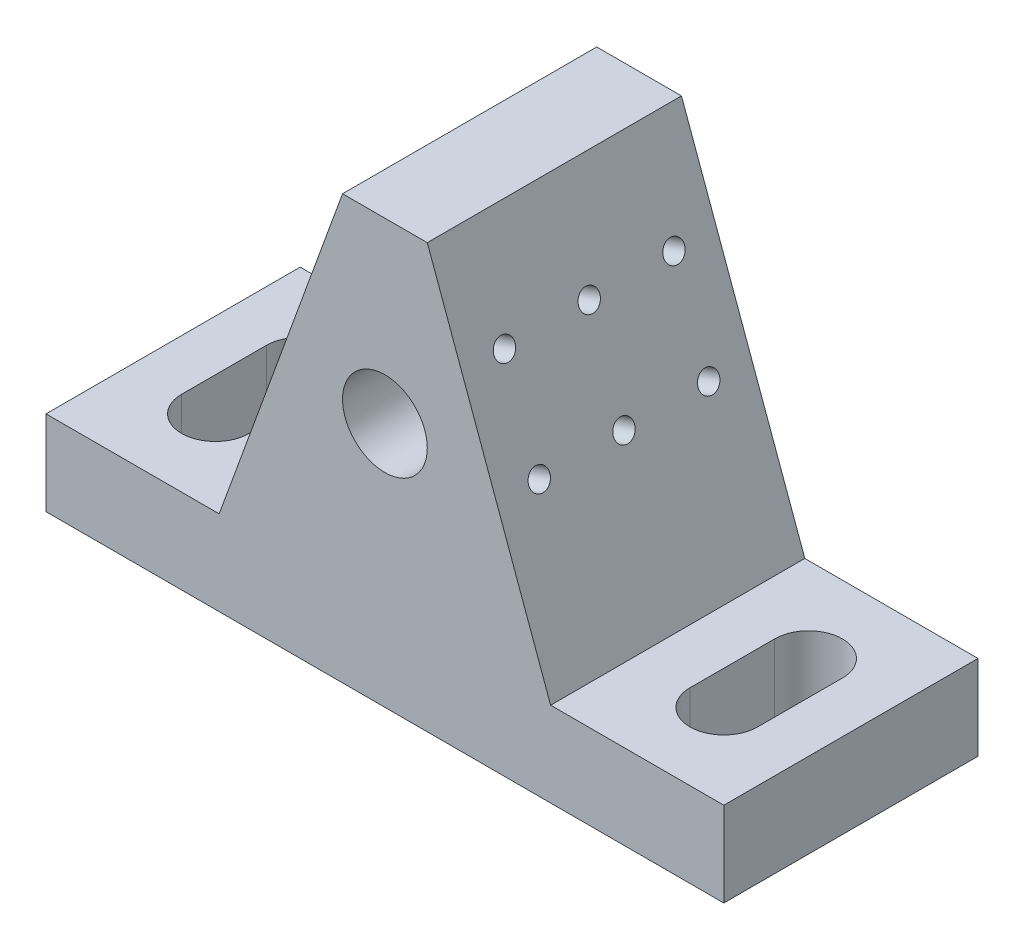
SolidWorks part; units mm, degrees
material "AISI 304"
ref_plane "Front Plane" through (0, 0, 0) normal (0, 0, 1) x (1, 0, 0)
ref_plane "Top Plane" through (0, 0, 0) normal (0, 1, 0) x (1, 0, 0)
ref_plane "Right Plane" through (0, 0, 0) normal (1, 0, 0) x (0, 0, -1)
sketch "Sketch1" plane through (0, 0, 0) normal (0, 0, 1) x (1, 0, 0)
  line L0 (0, 0) -> (0, 44.6241) construction
  line L1 (-40, 0) -> (40, 0)
  line L2 (40, 0) -> (40, 10)
  line L3 (-40, 0) -> (-40, 10)
  line L4 (40, 10) -> (19.5588, 10)
  line L5 (-40, 10) -> (-19.5588, 10)
  line L6 (19.5588, 10) -> (5, 50)
  line L7 (-19.5588, 10) -> (-5, 50)
  line L8 (5, 50) -> (-5, 50)
  dimension "D1" = 80
  dimension "D2" = 10
  dimension "D3" = 50
  dimension "D4" = 10
  dimension "D5" = 110
extrude "Boss Extrude" add sketch "Sketch1" along normal mid plane 30
sketch "Sketch2" plane through (0, 10, 0) normal (0, 1, 0) x (1, 0, 0)
  line L0 (30, -5) -> (30, 5) construction
  line L1 (26, -5) -> (26, 5)
  line L2 (34, -5) -> (34, 5)
  line L3 (40, 15) -> (19.5588, 15) construction
  arc A0 (26, -5) -> (34, -5) centre (30, -5) ccw
  arc A1 (34, 5) -> (26, 5) centre (30, 5) ccw
  point P2 (30, 0)
  dimension "D4" = 4
  dimension "D1" = 30
  dimension "D2" = 10
  dimension "D3" = 10
extrude "Slot Cut" cut sketch "Sketch2" against normal through all
mirror "Mirror4" about plane through (0, 0, 0) normal (1, 0, 0) of "Slot Cut"
sketch "Sketch3" plane through (0, 0, 15) normal (0, 0, 1) x (1, 0, 0)
  circle A0 centre (0, 29) radius 5
  dimension "D2" = 10
  dimension "D1" = 29
extrude "Guide Hole" cut sketch "Sketch3" against normal through all
hole_wizard "M3x0.5 Tapped Hole5" positions "Sketch16" profile "Sketch17" tap size "M3x0.5" standard "ANSI Metric"
sketch "Sketch16" plane through (20.4848, 7.4559, 0) normal (0.9397, 0.342, 0) x (0, 0, -1)
  line L0 (15, 2.7074) -> (15, 45.2745) construction
  line L1 (15, 27.2511) -> (-15, 27.2511) construction
  point P0 (-10, 21.2511)
  dimension "D1" = 25
  dimension "D2" = 6
sketch "Sketch17" plane through (13.2165, 27.4253, 10) normal (0, 0, 1) x (-0.342, 0.9397, 0)
  line L0 (0, 0) -> (0, 8.2511)
  line L1 (0, 8.2511) -> (1.25, 7.5)
  line L2 (1.25, 7.5) -> (1.25, 0)
  line L5 (1.25, 0) -> (0, 0)
  line L10 (0, 8.2511) -> (-1.25, 7.5) construction
  line L11 (0, -6.35) -> (0, 107.95) construction
  dimension "Tap Drill Dia." = 2.5
  dimension "Tap Drill Depth" = 7.5
  dimension "Drill Angle" = 118
cosmetic thread "Hole Thread7" parameters "D1"=6, "D2"=3
pattern_linear "LPattern2" count 3 spacing 10 along (0, 0, -1) count 2 spacing 12 along (-0.342, 0.9397, 0) of "M3x0.5 Tapped Hole5"
cosmetic thread "Hole Thread8" parameters "D1"=6, "D2"=3
cosmetic thread "Hole Thread9" parameters "D1"=6, "D2"=3
cosmetic thread "Hole Thread10" parameters "D1"=6, "D2"=3
cosmetic thread "Hole Thread11" parameters "D1"=6, "D2"=3
cosmetic thread "Hole Thread12" parameters "D1"=6, "D2"=3
